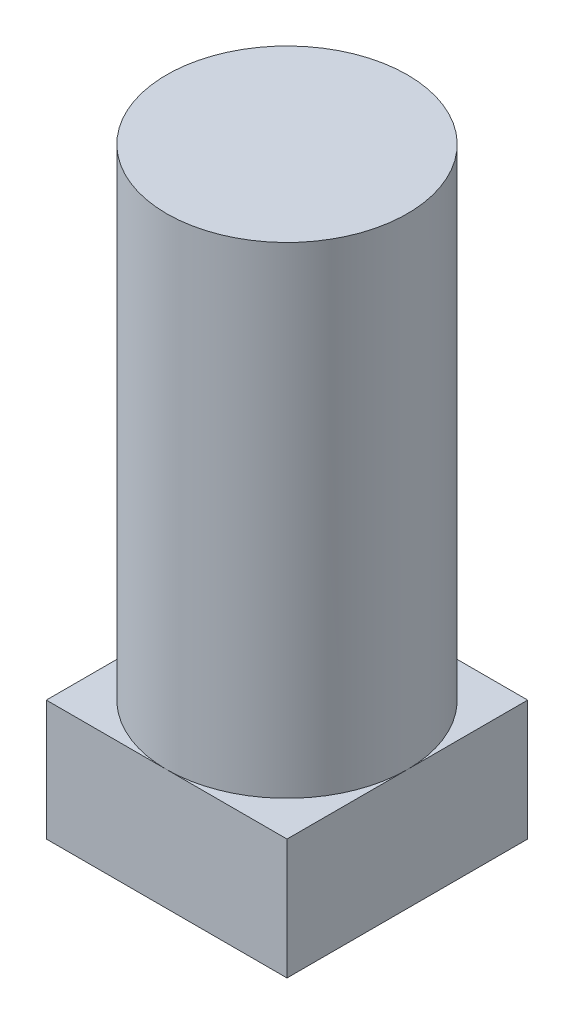
SolidWorks part; units mm, degrees
ref_plane "前视基准面" through (0, 0, 0) normal (0, 0, 1) x (1, 0, 0)
ref_plane "上视基准面" through (0, 0, 0) normal (0, 1, 0) x (1, 0, 0)
ref_plane "右视基准面" through (0, 0, 0) normal (1, 0, 0) x (0, 0, -1)
other "Configuration Table"
sketch "草图1" plane through (0, 0, 0) normal (0, 1, 0) x (1, 0, 0)
  circle A0 centre (0, 0) radius 5
  dimension "D1" = 10
extrude "凸台-拉伸1" add sketch "草图1" along normal blind 20
sketch "草图2" plane through (0, 0, 0) normal (0, -1, 0) x (1, 0, 0)
  line L1 (-5, -5) -> (5, -5)
  line L2 (-5, -5) -> (-5, 5)
  line L3 (-5, 5) -> (5, 5)
  line L4 (5, -5) -> (5, 5)
  line L5 (-5, -5) -> (5, 5) construction
  line L6 (-5, 5) -> (5, -5) construction
  point P0 (0, 0)
  dimension "D1" = 10
  dimension "D2" = 10
extrude "凸台-拉伸2" add sketch "草图2" along normal blind 5
equation "\"、\"=20"
